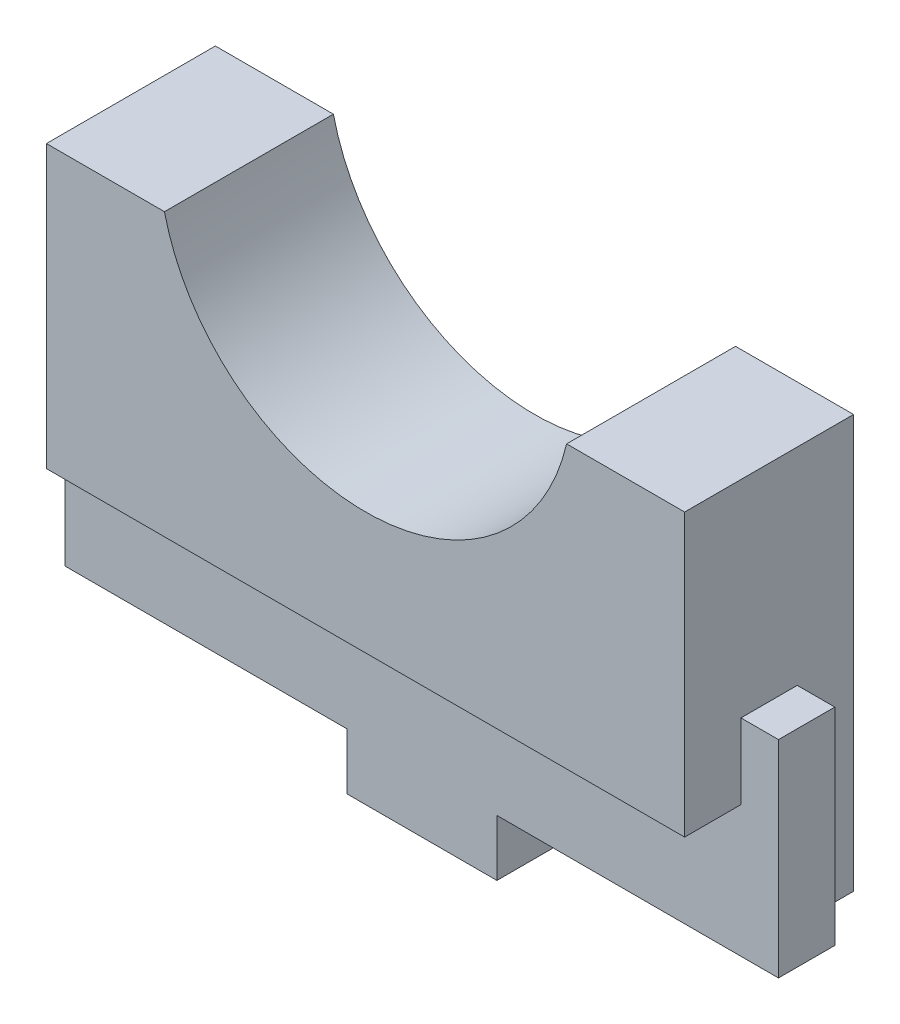
SolidWorks part; units mm, degrees
ref_plane "Front Plane" through (0, 0, 0) normal (0, 0, 1) x (1, 0, 0)
ref_plane "Top Plane" through (0, 0, 0) normal (0, 1, 0) x (1, 0, 0)
ref_plane "Right Plane" through (0, 0, 0) normal (1, 0, 0) x (0, 0, -1)
sketch "Sketch1" plane through (0, 0, 0) normal (0, 0, 1) x (1, 0, 0)
  line L0 (-17, 0) -> (17, 0) construction
  line L1 (0, 0) -> (0, -11) construction
  line L2 (-17, -2.5) -> (17, -2.5)
  line L4 (-17, -2.5) -> (-17, -24.5)
  line L5 (-17, -24.5) -> (17, -24.5)
  line L6 (17, -24.5) -> (17, -2.5)
  circle A0 centre (0, 0) radius 11
  dimension "D1" = 22
  dimension "D2" = 17
  dimension "D5" = 22
  dimension "D3" = 2.5
extrude "Boss-Extrude1" add sketch "Sketch1" along normal blind 9 contours A0 L2 L4 L5 L6
sketch "Sketch2" plane through (0, -24.5, 0) normal (0, -1, 0) x (1, 0, 0)
  line L1 (4, 0) -> (-4, 0)
  line L3 (4, 9) -> (-4, 9)
  line L4 (-4, 0) -> (-4, 9)
  line L5 (-17, 9) -> (17, 9) construction
  line L6 (4, 0) -> (4, 9)
  dimension "D1" = 8
  dimension "D2" = 9
  dimension "D3" = 4
  dimension "D4" = 4
extrude "Boss-Extrude2" add sketch "Sketch2" along normal blind 3
sketch "Sketch3" plane through (-17, 0, 0) normal (-1, 0, 0) x (0, 0, 1)
  line L0 (9, -24.5) -> (0, -24.5) construction
  line L1 (0, -2.5) -> (0, -24.5) construction
  line L7 (6, -13.5) -> (3, -13.5)
  line L8 (6, -13.5) -> (6, -24.5)
  line L9 (6, -24.5) -> (3, -24.5)
  line L10 (3, -13.5) -> (3, -24.5)
  line L11 (6, -13.5) -> (3, -24.5) construction
  line L12 (6, -24.5) -> (3, -13.5) construction
  point P12 (4.3664, -11.5604)
  dimension "D1" = 11
  dimension "D2" = 3
  dimension "D3" = 3
  dimension "D4" = 11
  dimension "D5" = 3
extrude "Boss-Extrude3" add sketch "Sketch3" along normal blind 2
sketch "Sketch4" plane through (17, 0, 0) normal (1, 0, 0) x (0, 0, -1)
  line L0 (0, -24.5) -> (0, -2.5) construction
  line L1 (-6, -13.5) -> (-3, -13.5)
  line L2 (-6, -13.5) -> (-6, -24.5)
  line L3 (-6, -24.5) -> (-3, -24.5)
  line L4 (-3, -13.5) -> (-3, -24.5)
  line L5 (-6, -13.5) -> (-3, -24.5) construction
  line L6 (-6, -24.5) -> (-3, -13.5) construction
  line L7 (-9, -24.5) -> (0, -24.5) construction
  point P0 (-4.5, -19)
  dimension "D1" = 3
  dimension "D2" = 3
  dimension "D3" = 11
extrude "Boss-Extrude4" add sketch "Sketch4" along normal blind 2
sketch "Sketch6" plane through (0, 0, 9) normal (0, 0, 1) x (1, 0, 0)
  line L0 (17, -24.5) -> (17, -2.5) construction
  line L1 (-17, -27.5) -> (17, -27.5)
  line L2 (-17, -27.5) -> (-17, -17.5)
  line L3 (-17, -17.5) -> (17, -17.5)
  line L4 (17, -27.5) -> (17, -17.5)
  dimension "D1" = 10
  dimension "D2" = 34
extrude "Cut-Extrude2" cut sketch "Sketch6" against normal blind 3
